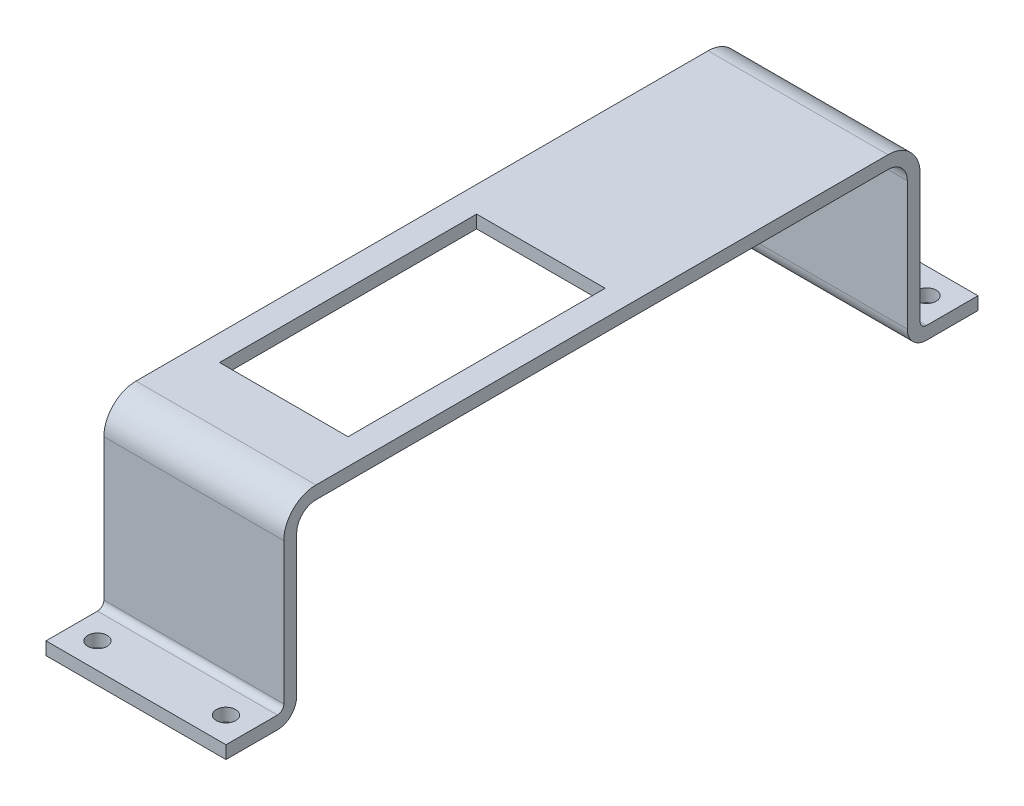
SolidWorks part; units mm, degrees
material "1060 Alloy"
ref_plane "Front Plane" through (0, 0, 0) normal (0, 0, 1) x (1, 0, 0)
ref_plane "Top Plane" through (0, 0, 0) normal (0, 1, 0) x (1, 0, 0)
ref_plane "Right Plane" through (0, 0, 0) normal (1, 0, 0) x (0, 0, -1)
sketch "Sketch1" plane through (0, 0, 0) normal (1, 0, 0) x (0, 0, -1)
  line L0 (3, 0) -> (11, 0)
  line L2 (-3, 26) -> (-92, 26)
  line L3 (-95, 23) -> (-95, 1)
  line L4 (-98, -2) -> (-106, -2)
  line L5 (0, 23) -> (0, 3)
  line L6 (2, 23) -> (2, 3)
  line L7 (-3, 28) -> (-92, 28)
  line L8 (-97, 23) -> (-97, 1)
  line L9 (-98, 0) -> (-106, 0)
  line L10 (3, 2) -> (11, 2)
  line L11 (11, 2) -> (11, 0)
  line L12 (-106, 0) -> (-106, -2)
  arc A0 (-3, 26) -> (0, 23) centre (-3, 23) cw
  arc A1 (-92, 26) -> (-95, 23) centre (-92, 23) ccw
  arc A2 (-95, 1) -> (-98, -2) centre (-98, 1) cw
  arc A3 (0, 3) -> (3, 0) centre (3, 3) ccw
  arc A4 (2, 3) -> (3, 2) centre (3, 3) ccw
  arc A5 (-3, 28) -> (2, 23) centre (-3, 23) cw
  arc A6 (-92, 28) -> (-97, 23) centre (-92, 23) ccw
  arc A7 (-97, 1) -> (-98, 0) centre (-98, 1) cw
  point P9 (0, 26)
  point P14 (-95, -2)
  dimension "D6" = 3
  dimension "D7" = 2
  dimension "D1" = 3
  dimension "D2" = 95
  dimension "D3" = 11
  dimension "D4" = 11
  dimension "D5" = 26
  dimension "D8" = 2
extrude "Boss-Extrude1" add sketch "Sketch1" along normal mid plane 28
sketch "Sketch2" plane through (0, 28, 0) normal (0, 1, 0) x (1, 0, 0)
  line L0 (0, 0) -> (0, -109.3837) construction
  line L1 (-10, -43) -> (10, -43)
  line L2 (-10, -43) -> (-10, -83)
  line L3 (-10, -83) -> (10, -83)
  line L4 (10, -43) -> (10, -83)
  line L5 (14, -97) -> (-14, -97) construction
  dimension "D1" = 14
  dimension "D2" = 20
  dimension "D3" = 40
  dimension "D4" = 10
extrude "Cut-Extrude1" cut sketch "Sketch2" against normal through all
sketch "Sketch3" plane through (0, 0, 0) normal (0, 1, 0) x (1, 0, 0)
  line L0 (0, 0) -> (0, -109.973) construction
  line L1 (14, -98) -> (14, -106) construction
  line L2 (14, -106) -> (-14, -106) construction
  line L3 (-14, -98) -> (-14, -106) construction
  circle A0 centre (10, -102) radius 1.5
  circle A1 centre (-10, -102) radius 1.5
  point P7 (14, -102)
  dimension "D1" = 3
  dimension "D2" = 3
  dimension "D5" = 4
  dimension "D3" = 4
  dimension "D4" = 4
  dimension "D6" = 4
extrude "Cut-Extrude2" cut sketch "Sketch3" against normal through all
sketch "Sketch4" plane through (0, 2, 0) normal (0, 1, 0) x (1, 0, 0)
  line L0 (0, 0) -> (0, 13.9416) construction
  line L1 (14, 11) -> (-14, 11) construction
  line L2 (14, 11) -> (14, 3) construction
  line L3 (-14, 11) -> (-14, 3) construction
  circle A0 centre (10, 7) radius 1.5
  circle A1 centre (-10, 7) radius 1.5
  dimension "D1" = 3
  dimension "D2" = 3
  dimension "D3" = 4
  dimension "D4" = 4
  dimension "D5" = 4
  dimension "D6" = 4
extrude "Cut-Extrude3" cut sketch "Sketch4" against normal through all
